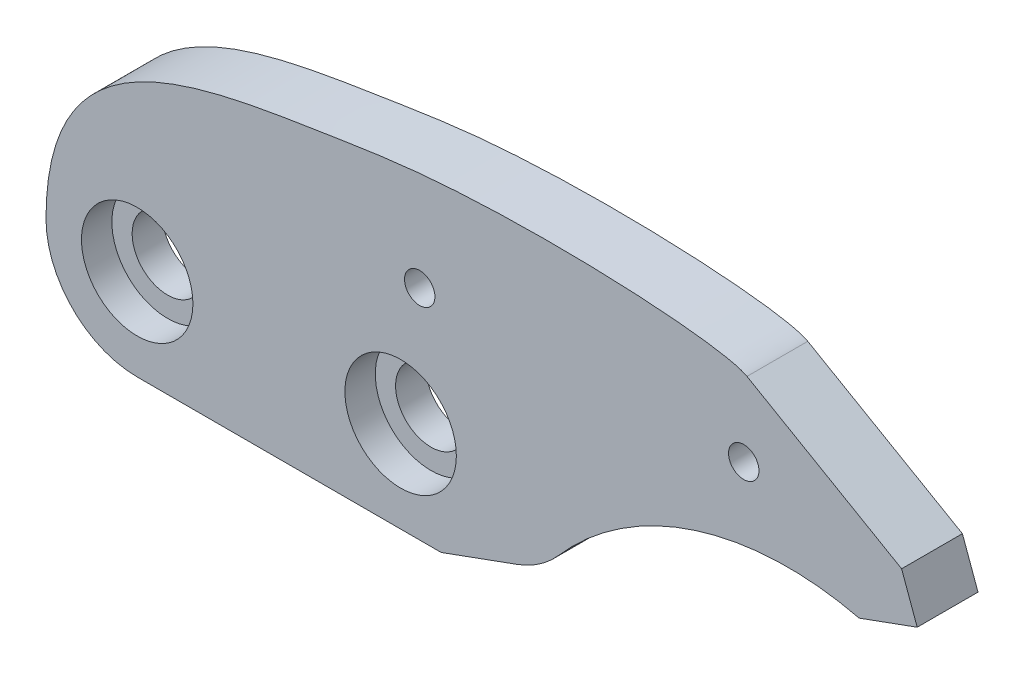
SolidWorks part; units mm, degrees
material "Acrylic (Medium-high impact)"
ref_plane "Front Plane" through (0, 0, 0) normal (0, 0, 1) x (1, 0, 0)
ref_plane "Top Plane" through (0, 0, 0) normal (0, 1, 0) x (1, 0, 0)
ref_plane "Right Plane" through (0, 0, 0) normal (1, 0, 0) x (0, 0, -1)
ref_plane "Plane1"
sketch "Sketch1" plane through (0, 0, 0) normal (0, 0, 1) x (1, 0, 0)
  line L0 (0, -9) -> (30, -9)
  line L3 (30, -9) -> (76.9846, 8.101)
  line L4 (26.8261, 9) -> (32.9825, -7.9145) construction
  line L5 (0, -9) -> (0, 9) construction
  line L14 (76.9846, 8.101) -> (75.4455, 12.3296)
  line L15 (75.4455, 12.3296) -> (60.1836, 21.1411)
  line L16 (60.1836, 21.1411) -> (26.8261, 9)
  line L17 (26.8261, 9) -> (0, 9)
  line L18 (0, 0) -> (26, 0) construction
  arc A0 (0, 9) -> (0, -9) centre (0, 0) ccw
  circle A1 centre (0, 0) radius 3.5
  circle A2 centre (26, 0) radius 3.5
  dimension "D7" = 7
  dimension "D1" = 18
  dimension "D2" = 160
  dimension "D3" = 140
  dimension "D4" = 50
  dimension "D5" = 4.5
  dimension "D6" = 30
  dimension "D11" = 26
extrude "Extrusion1" add sketch "Sketch1" along normal blind 6
ref_plane "Plane3"
sketch "Sketch3" plane through (0, 0, 0) normal (0, 0, -1) x (-1, 0, 0)
  line L0 (-53.9617, 5.0423) -> (-55.6718, 0.3438) construction
  line L1 (-30, -9) -> (-76.9846, 8.101) construction
  line L2 (-64.2224, -23.1485) -> (-55.6718, 0.3438) construction
  circle A0 centre (-64.2224, -23.1485) radius 30
  point P2 (-53.9617, 5.0423)
  dimension "D1" = 60
  dimension "D2" = 5
  dimension "D3" = 28
extrude "Extrusion3" cut sketch "Sketch3" against normal blind 10
sketch "Sketch5" plane through (0, 0, 0) normal (0, 0, -1) x (-1, 0, 0)
  line L0 (-61.2126, -14.8792) -> (-52.7246, 8.4412) construction
  line L1 (-30, -9) -> (-76.9846, 8.101) construction
  circle A0 centre (-61.3407, -15.2313) radius 25
  arc A1 (-40.0888, -5.328) -> (-71.2549, 6.0156) centre (-64.2224, -23.1485) ccw construction
  point P6 (-53.9617, 5.0423)
  dimension "D1" = 50
fillet "Fillet2" radius 10 1 edges at (40.0888, -5.328, 3)
sketch "Sketch6" plane through (0, 0, 0) normal (0, 0, -1) x (-1, 0, 0)
  line L0 (9, 0) -> (9, -7.9217) construction
  line L7 (-37.4748, -6.2794) -> (-30, -9)
  line L8 (-30, -9) -> (0, -9)
  line L9 (0, 9) -> (-26.8261, 9)
  line L10 (-26.8261, 9) -> (-60.1836, 21.1411)
  line L11 (-60.1836, 21.1411) -> (-75.4455, 12.3296)
  line L12 (-75.4455, 12.3296) -> (-76.9846, 8.101)
  line L13 (-76.9846, 8.101) -> (-71.2549, 6.0156)
  line L14 (-37.4748, -6.2794) -> (-30, -9)
  line L15 (-30, -9) -> (0, -9)
  line L16 (0, 9) -> (-26.8261, 9)
  line L17 (-26.8261, 9) -> (-60.1836, 21.1411)
  line L18 (-60.1836, 21.1411) -> (-75.4455, 12.3296)
  line L19 (-75.4455, 12.3296) -> (-76.9846, 8.101)
  line L20 (-76.9846, 8.101) -> (-71.2549, 6.0156)
  arc A3 (-41.5965, -3.449) -> (-71.2549, 6.0156) centre (-64.2224, -23.1485) ccw
  arc A4 (-41.5965, -3.449) -> (-37.4748, -6.2794) centre (-34.0546, 3.1175) ccw
  arc A5 (0, -9) -> (0, 9) centre (0, 0) ccw
  arc A6 (-41.5965, -3.449) -> (-71.2549, 6.0156) centre (-64.2224, -23.1485) ccw
  arc A7 (-41.5965, -3.449) -> (-37.4748, -6.2794) centre (-34.0546, 3.1175) ccw
  arc A8 (0, -9) -> (0, 9) centre (0, 0) ccw
  spline S0 degree 3 poles (-60.1836, 21.1411) (-57.583, 22.6426) (-35.7854, 23.8386) (-8.3771, 19.44) (9, 16.914) (9, 0) knots 0 0 0 0 0.435384 0.535384 1 1 1 1
  line M19 (0, 9) -> (-26.8261, 9)
  line M20 (-26.8261, 9) -> (-60.1836, 21.1411)
  dimension "D1" = 0
extrude "Boss-Extrude1" add sketch "Sketch6" against normal up to surface (6 mm away) contours S0 A8 M20 M19 up to face at (40.9622, 4.1745, 6)
sketch "Sketch7" plane through (0, 0, 0) normal (0, 0, -1) x (-1, 0, 0)
  circle A0 centre (0, 0) radius 5.5
  circle A1 centre (-26, 0) radius 5.5
  dimension "D1" = 11
sketch "Sketch8" plane through (0, 0, 0) normal (0, 0, -1) x (-1, 0, 0)
  line L0 (-76.9846, 8.101) -> (-59.8656, 13.6633) construction
  line L1 (-75.4455, 12.3296) -> (-60.1836, 21.1411) construction
  line L2 (-59.8656, 13.6633) -> (-27.8851, 12.5465) construction
  circle A0 centre (-59.8656, 13.6633) radius 1.5
  circle A1 centre (-27.8851, 12.5465) radius 1.5
  dimension "D3" = 3
  dimension "D5" = 160
  dimension "D1" = 12
  dimension "D2" = 18
  dimension "D4" = 32
extrude "Cut-Extrude1" cut sketch "Sketch8" against normal blind 14
extrude "Cut-Extrude2" cut sketch "Sketch7" along normal blind 3 from surface at -6 starting at face at (61.3656, 13.6633, 6)
